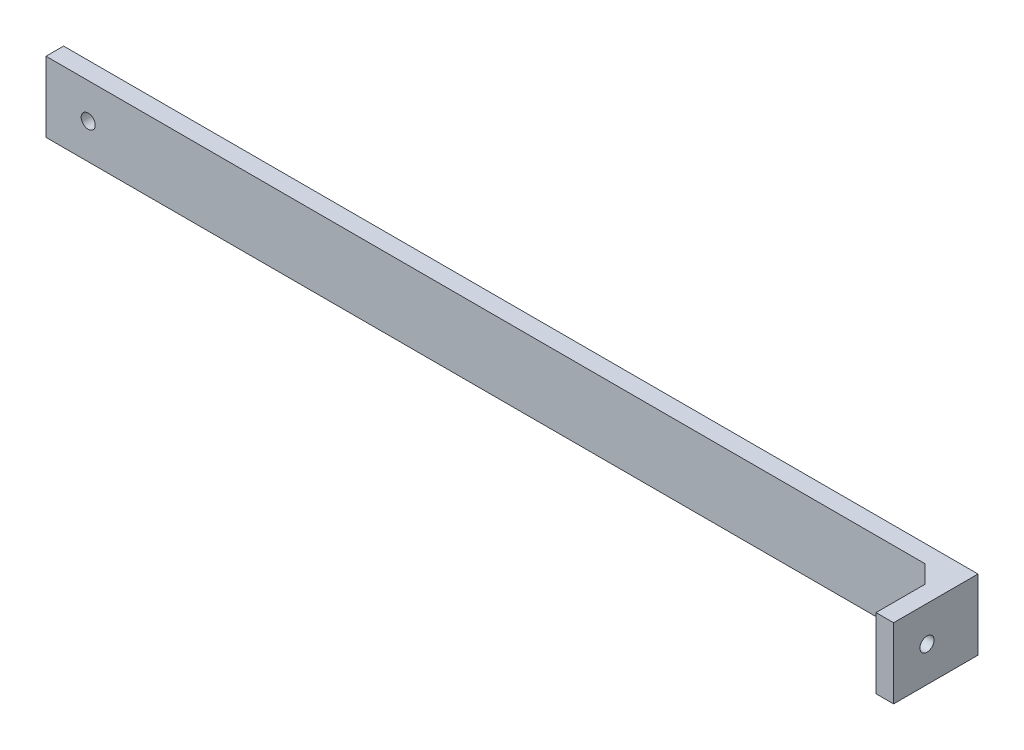
SolidWorks part; units mm, degrees
ref_plane "Front Plane" through (0, 0, 0) normal (0, 0, 1) x (1, 0, 0)
ref_plane "Top Plane" through (0, 0, 0) normal (0, 1, 0) x (1, 0, 0)
ref_plane "Right Plane" through (0, 0, 0) normal (1, 0, 0) x (0, 0, -1)
sketch "Sketch1" plane through (0, 0, 0) normal (0, 0, 1) x (1, 0, 0)
  line L1 (-130, -10) -> (130, -10)
  line L2 (-130, -10) -> (-130, 10)
  line L3 (-130, 10) -> (130, 10)
  line L4 (130, -10) -> (130, 10)
  line L5 (-130, -10) -> (130, 10) construction
  line L6 (-130, 10) -> (130, -10) construction
  point P0 (0, 0)
  dimension "D1" = 20
  dimension "D2" = 260
extrude "Boss-Extrude1" add sketch "Sketch1" along normal blind 5
sketch "Sketch2" plane through (0, 0, 5) normal (0, 0, 1) x (1, 0, 0)
  line L0 (-130, -10) -> (130, -10) construction
  line L1 (130, 10) -> (125, 10)
  line L2 (130, 10) -> (130, -10)
  line L3 (130, -10) -> (125, -10)
  line L4 (125, 10) -> (125, -10)
  dimension "D1" = 5
extrude "Boss-Extrude2" add sketch "Sketch2" along normal blind 19
sketch "Sketch3" plane through (130, 0, 0) normal (1, 0, 0) x (0, 0, -1)
  line L0 (-24, -10) -> (0, -10) construction
  line L1 (-24, -10) -> (-24, 10) construction
  circle A0 centre (-14.5, 0) radius 2
  dimension "D1" = 4
  dimension "D2" = 10
  dimension "D3" = 9.5
extrude "Cut-Extrude1" cut sketch "Sketch3" against normal through all
sketch "Sketch4" plane through (125, 0, 0) normal (-1, 0, 0) x (0, 0, 1)
  line L1 (5, -10) -> (10, -10)
  line L2 (5, -10) -> (5, -5)
  line L3 (5, -5) -> (10, -5)
  line L4 (10, -10) -> (10, -5)
  line L5 (5, 10) -> (10, 10)
  line L6 (5, 10) -> (5, 5)
  line L7 (5, 5) -> (10, 5)
  line L8 (10, 10) -> (10, 5)
  dimension "D1" = 5
  dimension "D2" = 5
  dimension "D3" = 5
  dimension "D4" = 5
extrude "Boss-Extrude3" add sketch "Sketch4" along normal blind 5
sketch "Sketch5" plane through (0, -10, 0) normal (0, -1, 0) x (1, 0, 0)
  line L0 (120, 5) -> (125, 10)
  line L1 (125, 10) -> (120, 10)
  line L2 (120, 10) -> (120, 5)
extrude "Cut-Extrude2" cut sketch "Sketch5" against normal through all
sketch "Sketch6" plane through (0, 0, 0) normal (0, 0, -1) x (-1, 0, 0)
  line L0 (-130, -10) -> (-130, 10) construction
  line L1 (130, -10) -> (-130, -10) construction
  circle A0 centre (118, 0) radius 2
  dimension "D1" = 4
  dimension "D2" = 248
  dimension "D3" = 10
extrude "Cut-Extrude3" cut sketch "Sketch6" against normal through all
